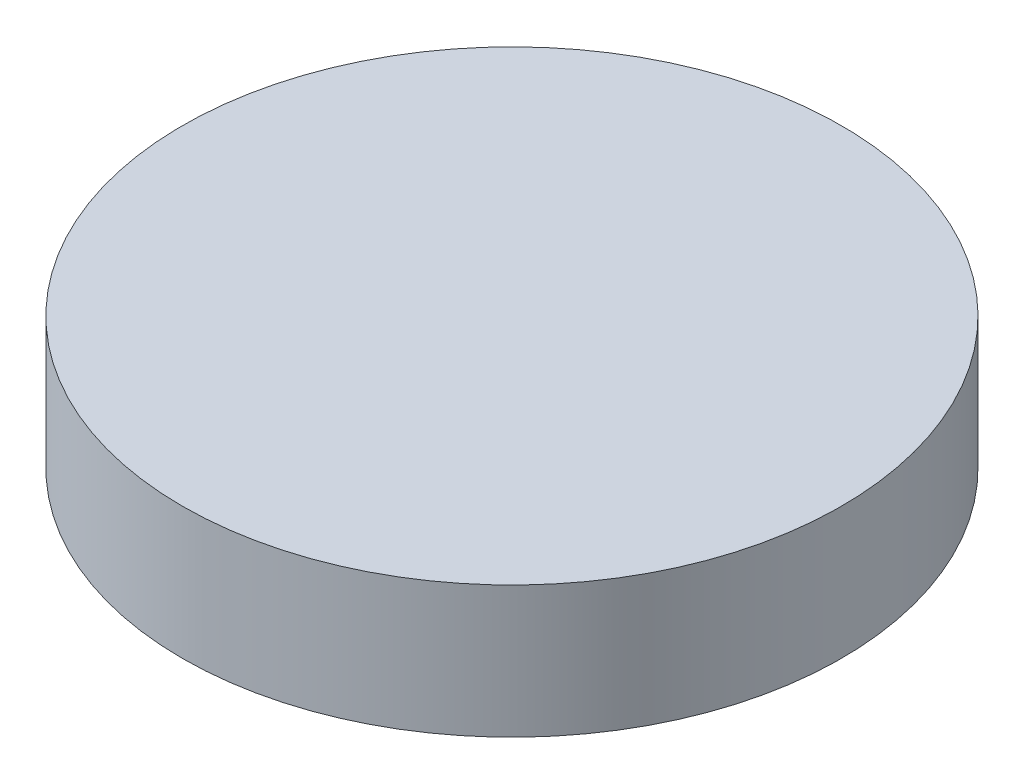
SolidWorks part; units mm, degrees
ref_plane "Front" through (0, 0, 0) normal (0, 0, 1) x (1, 0, 0)
ref_plane "Top" through (0, 0, 0) normal (0, 1, 0) x (1, 0, 0)
ref_plane "Right" through (0, 0, 0) normal (1, 0, 0) x (0, 0, -1)
sketch "Sketch2" plane through (0, 0, 0) normal (0, 1, 0) x (1, 0, 0)
  circle A2 centre (0, 0) radius 3.175
  dimension "D1" = 6.35
extrude "Boss-Extrude1" add sketch "Sketch2" along normal blind 1.27
